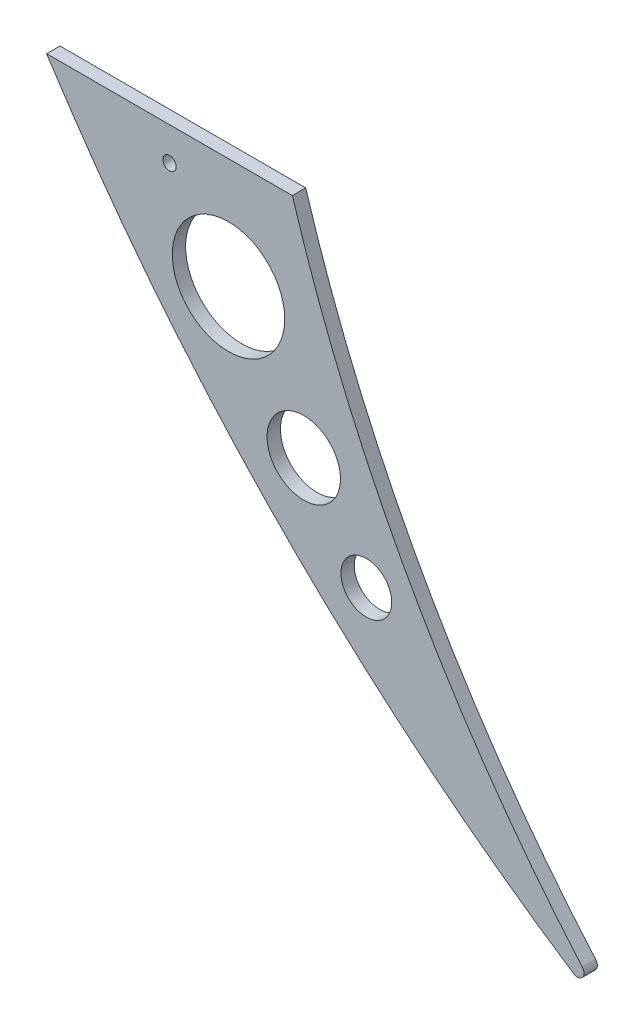
SolidWorks part; units mm, degrees
ref_plane "Alzado" through (0, 0, 0) normal (0, 0, 1) x (1, 0, 0)
ref_plane "Planta" through (0, 0, 0) normal (0, 1, 0) x (1, 0, 0)
ref_plane "Vista lateral" through (0, 0, 0) normal (1, 0, 0) x (0, 0, -1)
sketch "Croquis1" plane through (0, 0, 0) normal (0, 0, 1) x (1, 0, 0)
  line L0 (4031.0865, 1267.9986) -> (3994.2208, 1267.9986)
  circle A0 centre (4042.1825, 1222.5895) radius 3.8118
  circle A1 centre (4021.5049, 1251.3749) radius 8.4337
  arc A2 (3994.2208, 1267.9986) -> (4073.2937, 1187.9986) centre (4221.5649, 1413.6297) ccw
  arc A3 (4031.0865, 1267.9986) -> (4074.598, 1189.4899) centre (4238.0678, 1331.401) ccw
  arc A4 (4073.2937, 1187.9986) -> (4074.598, 1189.4899) centre (4073.8429, 1188.8344) ccw
  circle A5 centre (4032.7949, 1234.7772) radius 5.5064
  circle A6 centre (4012.6537, 1262.9986) radius 1
  dimension "D1" = 5
extrude "Saliente-Extruir1" add sketch "Croquis1" along normal blind 2
